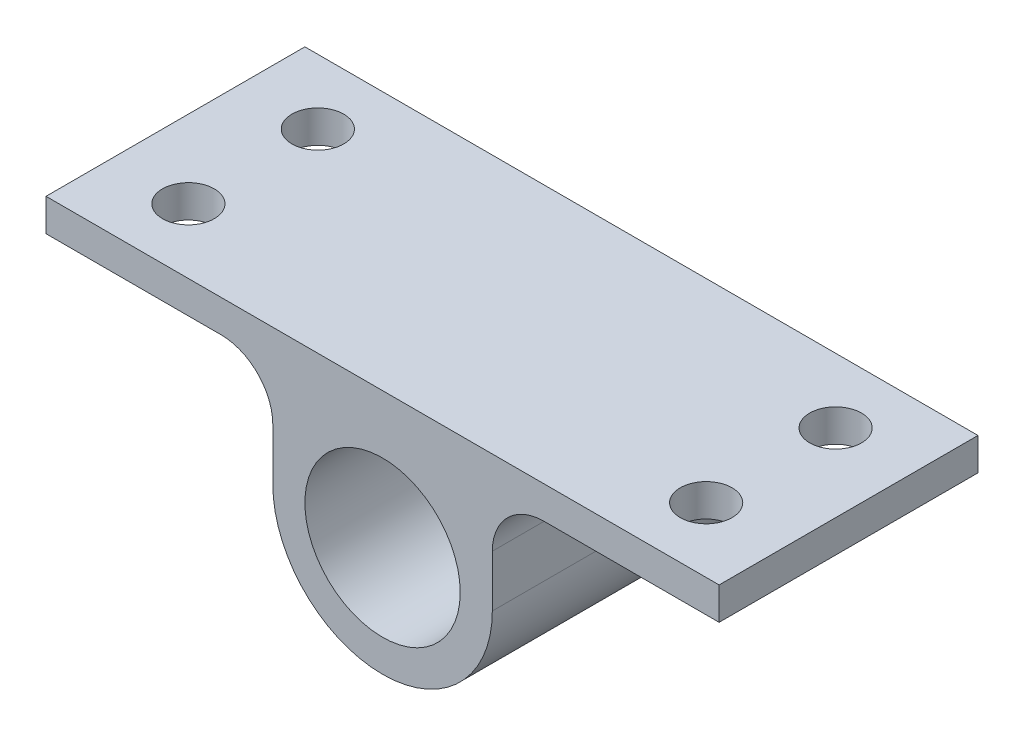
SolidWorks part; units mm, degrees
ref_plane "Front Plane" through (0, 0, 0) normal (0, 0, 1) x (1, 0, 0)
ref_plane "Top Plane" through (0, 0, 0) normal (0, 1, 0) x (1, 0, 0)
ref_plane "Right Plane" through (0, 0, 0) normal (1, 0, 0) x (0, 0, -1)
sketch "Sketch1" plane through (0, 0, 0) normal (0, 0, 1) x (1, 0, 0)
  line L0 (-51.0741, -18.9689) -> (-51.0741, -6.2689)
  line L1 (-106.7001, 14.3813) -> (58.3999, 14.3813)
  line L2 (-106.7001, 14.3813) -> (-106.7001, 6.4311)
  line L3 (-106.7001, 6.4311) -> (-63.7741, 6.4311)
  line L4 (58.3999, 14.3813) -> (58.3999, 6.4311)
  line L5 (2.7739, -18.9689) -> (2.7739, -6.2689)
  line L6 (15.4739, 6.4311) -> (58.3999, 6.4311)
  circle A0 centre (-24.1501, -18.9689) radius 19.05
  arc A1 (-51.0741, -18.9689) -> (2.7739, -18.9689) centre (-24.1501, -18.9689) ccw
  arc A2 (2.7739, -6.2689) -> (15.4739, 6.4311) centre (15.4739, -6.2689) cw
  arc A3 (-51.0741, -6.2689) -> (-63.7741, 6.4311) centre (-63.7741, -6.2689) ccw
  point P4 (-24.1501, 14.3813)
  point P14 (2.7739, 6.4311)
  dimension "D4" = 33.3502
  dimension "D5" = 38.1
  dimension "D6" = 53.848
  dimension "D7" = 12.7
  dimension "D1" = 165.1
  dimension "D2" = 7.9502
  dimension "D3" = 82.55
extrude "Boss-Extrude1" add sketch "Sketch1" along normal mid plane 63.5
sketch "Sketch3" plane through (0, 14.3813, 0) normal (0, 1, 0) x (1, 0, 0)
  line L0 (-24.1501, 0) -> (-24.1501, -47.3228)
  circle A0 centre (-87.6501, 15.875) radius 6.35
  circle A1 centre (-87.6501, -15.875) radius 6.35
  circle A2 centre (39.3499, -15.875) radius 6.35
  circle A3 centre (39.3499, 15.875) radius 6.35
  dimension "D1" = 19.05
  dimension "D3" = 31.75
  dimension "D2" = 19.05
  dimension "D4" = 15.875
extrude "Cut-Extrude1" cut sketch "Sketch3" against normal through all contours A1 | A0 | A3 | A2
